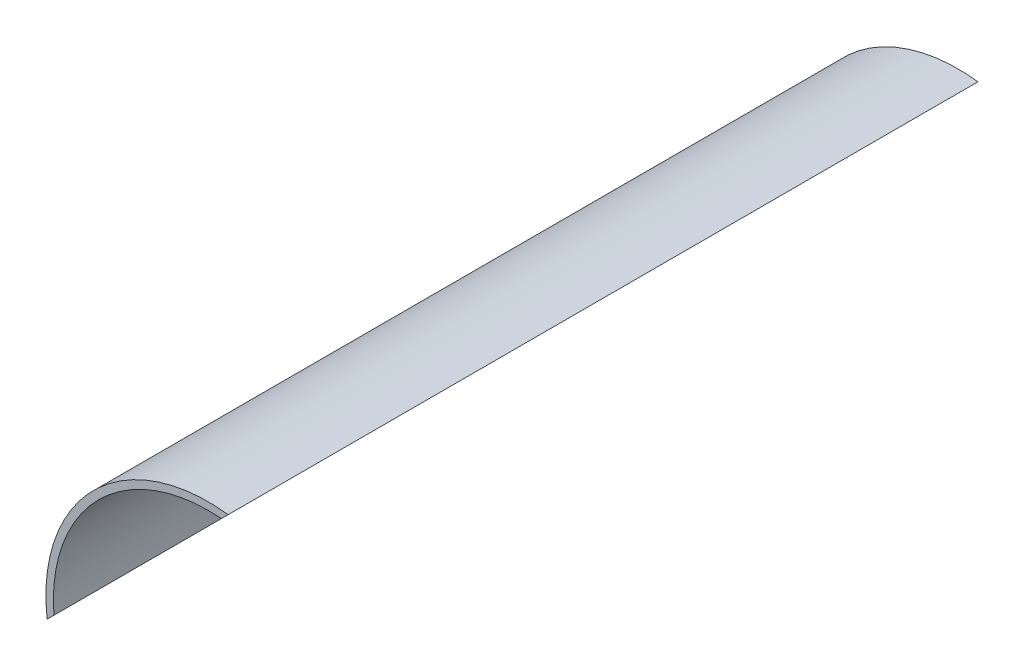
SolidWorks part; units mm, degrees
material "Polyetheretherketone (PEEK)"
ref_plane "Front Plane" through (0, 0, 0) normal (0, 0, 1) x (1, 0, 0)
ref_plane "Top Plane" through (0, 0, 0) normal (0, 1, 0) x (1, 0, 0)
ref_plane "Right Plane" through (0, 0, 0) normal (1, 0, 0) x (0, 0, -1)
sketch "Sketch1" plane through (0, 0, 0) normal (0, 0, 1) x (1, 0, 0)
  circle A0 centre (0, 0) radius 62
  circle A1 centre (0, 0) radius 65
  dimension "D1" = 124
  dimension "D2" = 3
extrude "Boss-Extrude1" add sketch "Sketch1" along normal blind 300
sketch "Sketch2" plane through (0, 0, 0) normal (0, 1, 0) x (1, 0, 0)
  line L0 (62, 0) -> (-62, 0) construction
  circle A0 centre (0, -224) radius 1
  circle A1 centre (0, -264) radius 1
  dimension "D1" = 2
  dimension "D3" = 2
  dimension "D2" = 224
  dimension "D4" = 40
ref_plane "Plane1" through (0, 0, 0) normal (-0.7071, 0.7071, 0) x (0.7071, 0.7071, 0)
ref_plane "Plane2" through (-28.2843, 28.2843, 0) normal (-0.7071, 0.7071, 0) x (0.7071, 0.7071, 0)
sketch "Sketch4" plane through (-28.2843, 28.2843, 0) normal (-0.7071, 0.7071, 0) x (0.7071, 0.7071, 0)
  line L0 (-65, 0) -> (-65, -300) construction
  line L1 (-65, 0) -> (65, 0)
  line L2 (-65, 0) -> (-65, -300)
  line L3 (-65, -300) -> (65, -300)
  line L4 (65, 0) -> (65, -300)
  line L5 (65, -300) -> (65, 0) construction
  line L6 (65, 0) -> (-65, 0) construction
  dimension "D1" = 0
  dimension "D2" = 300
extrude "Cut-Extrude4" cut sketch "Sketch4" against normal blind 516
sketch "Sketch5" plane through (0, 0, 0) normal (0, 0, -1) x (-1, 0, 0)
  line L1 (0, 0) -> (45.9619, 45.9619)
  line L2 (1, 0) -> (-1, 0) construction
  line L3 (45.9619, 45.9619) -> (84.5805, 7.3433) construction
  circle A0 centre (0, 0) radius 65 construction
